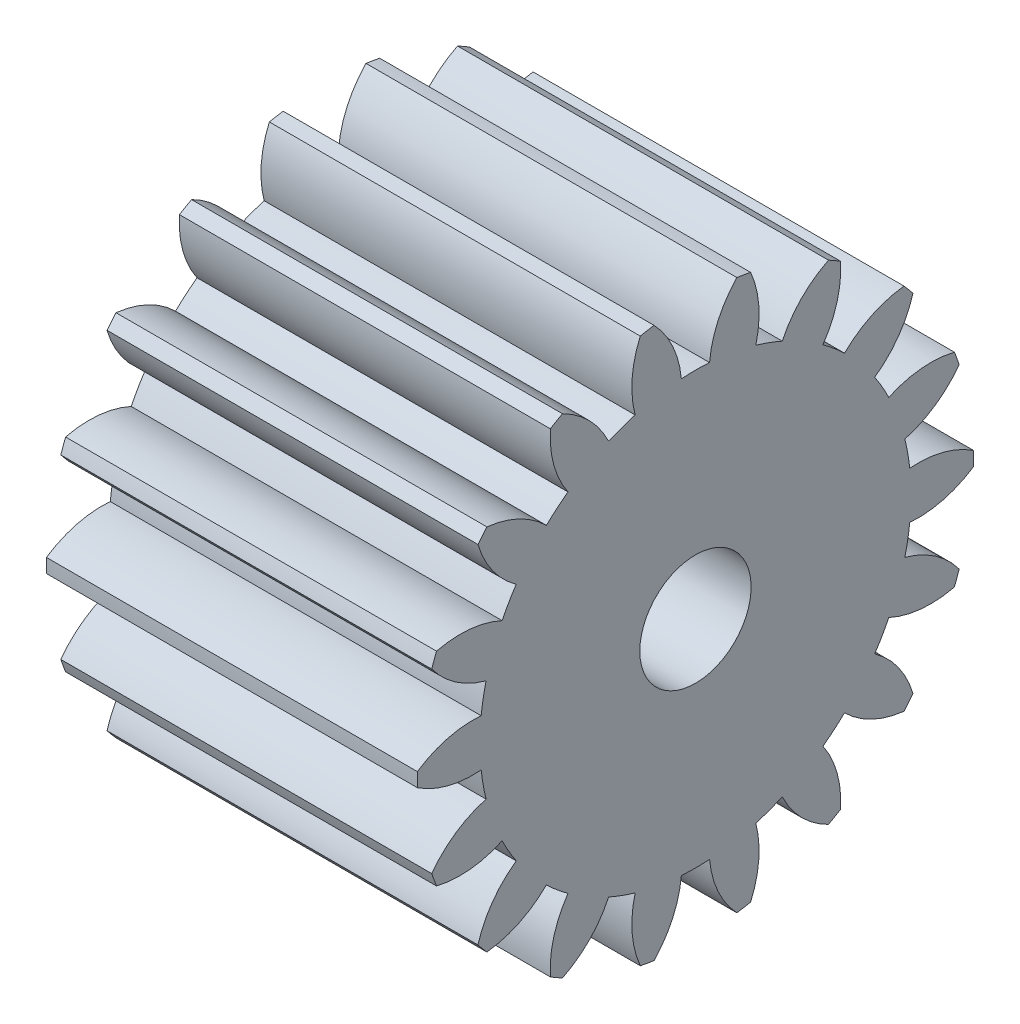
SolidWorks part; units mm, degrees
ref_plane "Plane1" through (0, 0, 0) normal (0, 0, 1) x (1, 0, 0)
ref_plane "Plane2" through (0, 0, 0) normal (0, 1, 0) x (1, 0, 0)
ref_plane "Plane3" through (0, 0, 0) normal (1, 0, 0) x (0, 0, -1)
other "Configuration Table"
sketch "HoldingSke" plane through (0, 0, 0) normal (0, 1, 0) x (1, 0, 0)
  line L0 (0, 0) -> (0.634, -0.206)
  line L1 (-15, 0) -> (100, 0) construction
  line L2 (0, 0) -> (-2.1039, 2.3779)
  line L3 (0, 0) -> (-11.863, 4.5341)
  line L4 (0, 0) -> (8.2133, 2.6687)
  line L5 (0, 0) -> (-46.8476, -17.4728)
  line L6 (0, 0) -> (-16.5793, -11.1861)
  line L7 (-2.1039, 2.3779) -> (8.6586, 51.2059)
  line L8 (-76.2, 54.61) -> (-75.2, 54.61)
  line L9 (-71.009, 38.7566) -> (-53.1078, 45.2721)
  line L10 (-76.2, 71.12) -> (104.1128, 71.12)
  line L11 (0, 0) -> (-20, 0)
  line L12 (-76.2, 101.6) -> (-76.147, 101.6)
  line L13 (24.9733, 27.94) -> (52.9518, 28.4284)
  line L14 (24.9733, 27.94) -> (24.9743, 27.94)
  line L15 (24.9733, 27.94) -> (100.4006, 29.5858)
  line L16 (-63.627, -1.5) -> (-12.827, -1.5)
  circle A0 centre (0, 0) radius 3
  circle A1 centre (0, 0) radius 11.624
  circle A2 centre (0, 0) radius 37.5
  circle A3 centre (0, 0) radius 3
  dimension "MHD" = 23.248
  dimension "Hub_dia" = 75
  dimension "Bore" = 6
  dimension "MBD" = 6
  dimension "Num_teeth" = 18
  dimension "Pitch" = 0.6667
  dimension "Overall_len" = 50
  dimension "Show_teeth" = 18
  dimension "Thickness" = 20
  dimension "OAL" = 50.0001
  dimension "T_dim" = 1
  dimension "Ap" = 20
  dimension "H" = 19.05
  dimension "Pitch_radius" = 180.3128
  dimension "Width" = 20
  dimension "Backlash" = 0.053
  dimension "Addendum_fac" = 1
  dimension "Dedendum_fac" = 1.25
  dimension "Clearance_fac" = 0.25
  dimension "Dedendum_add" = 0.001
  dimension "Module" = 1.5
sketch "BasProSke" plane through (0, 0, 0) normal (0, 1, 0) x (1, 0, 0)
  line L0 (-10, 0) -> (60, 0) construction
  line L1 (0, 0) -> (0, 15)
  line L2 (0, 0) -> (20, 0)
  line L3 (20, 0) -> (20, 15)
  line L4 (20, 15) -> (0, 15)
  dimension "Thickness" = 20
  dimension "Diameter" = 30
revolve "Base-Revolve" add sketch "BasProSke" angle 360 about L0
sketch "TooCutSke" plane through (0, 0, 0) normal (1, 0, 0) x (0, 0, -1)
  line L1 (0, 0) -> (0, 107) construction
  line L2 (0, 0) -> (-1.2693, 13.4402) construction
  line L3 (0, 0) -> (-4.6734, 26.504) construction
  line L4 (-1.2693, 13.4402) -> (-2.3367, 13.252) construction
  arc A0 (0.76, 11.5991) -> (-0.76, 11.5991) centre (0, 0) ccw
  arc A1 (2.2542, 14.8553) -> (-2.2542, 14.8553) centre (0, 0) ccw
  circle A2 centre (0, 0) radius 13.5 construction
  circle A3 centre (0, 0) radius 12.6859 construction
  arc A4 (-0.76, 11.5991) -> (-2.2542, 14.8553) centre (-6.1371, 11.1026) ccw
  arc A5 (2.2542, 14.8553) -> (0.76, 11.5991) centre (6.1371, 11.1026) ccw
  dimension "Root_dia" = 23.248
  dimension "Overcut_dia" = 30.0508
  dimension "Pitch_dia" = 27
  dimension "Base_dia" = 25.3717
  dimension "Flank_rad" = 5.4
  dimension "Half_ang" = 10
  dimension "Half_CT" = 1.0839
extrude "ToothCut" cut sketch "TooCutSke" along normal through all
fillet "Breaks" [suppressed] radius 0.03
fillet "RootFillets" [suppressed] radius 0.376
pattern_circular "TeethCuts" count 18 every 20 about axis through (-10, 0, 0) along (1, 0, 0) of "ToothCut", "RootFillets", "Breaks"
sketch "HubNeaOneSke" plane through (0, 0, 0) normal (-1, 0, 0) x (0, 0, 1)
  circle A0 centre (0, 0) radius 11.624
  dimension "Diameter" = 23.248
extrude "HubNearOne" [suppressed] add sketch "HubNeaOneSke" along normal blind 30.0001
sketch "HubNeaBotSke" plane through (0, 0, 0) normal (-1, 0, 0) x (0, 0, 1)
  circle A0 centre (0, 0) radius 11.624
  dimension "Diameter" = 23.248
extrude "HubNearBoth" [suppressed] add sketch "HubNeaBotSke" along normal blind 15
ref_plane "FarPln" through (20, 0, 0) normal (1, 0, 0) x (0, 0, -1)
sketch "HubFarSke" plane through (20, 0, 0) normal (1, 0, 0) x (0, 0, -1)
  circle A0 centre (0, 0) radius 11.624
  dimension "Diameter" = 23.248
extrude "HubFar" [suppressed] add sketch "HubFarSke" along normal blind 15
sketch "BorSke" plane through (0, 0, 0) normal (1, 0, 0) x (0, 0, -1)
  circle A0 centre (0, 0) radius 3
  dimension "Diameter" = 6
extrude "Bore" cut sketch "BorSke" along normal mid plane 100.0001
sketch "KeySke" plane through (0, 0, 0) normal (1, 0, 0) x (0, 0, -1)
  line L0 (-1, 0) -> (-1, 4)
  line L1 (-1, 4) -> (1, 4)
  line L2 (1, 4) -> (1, 0)
  line L3 (0, 0) -> (0, 34) construction
  line L4 (-1, 0) -> (1, 0)
  dimension "Offset" = 4
extrude "Keyway" [suppressed] cut sketch "KeySke" along normal mid plane 100.0001
pattern_circular "Keyway2" [suppressed] count 2 every 90 about axis through (-10, 0, 0) along (1, 0, 0)
equation "' \"Module@HoldingSke\" = 6.35"
equation "' \"Num_teeth@HoldingSke\" = 12"
equation "' \"Ap@HoldingSke\" =  20"
equation "' \"Ap@HoldingSke\" = 20"
equation "' \"Width@HoldingSke\" = 0.5 * 25.4"
equation "' \"Hub_dia@HoldingSke\"= 1 * 25.4"
equation "' \"Hub_dia@HoldingSke\" = 1 * 25.4"
equation "' \"Overall_len@HoldingSke\" = 1.0 * 25.4"
equation "' \"Bore@HoldingSke\" = 0.75 * 25.4"
equation "' \"T_dim@HoldingSke\" = 0.1 * 25.4"
equation "' \"Width@KeySke\" = 0.25 * 25.4"
equation "' \"Show_teeth@HoldingSke\" = 13"
equation "' \"Backlash@HoldingSke\" = 0.009 * 25.4"
equation "' \"Addendum_fac@HoldingSke\" = 1.0"
equation "' \"Dedendum_fac@HoldingSke\" = 1.25"
equation "' \"Dedendum_add@HoldingSke\" = 0.00005 * 25.4"
equation "' \"Clearance_fac@HoldingSke\" = 0.25"
equation "\"Pitch@HoldingSke\" = 1 / \"Module@HoldingSke\""
equation "\"Overcut_dia@TooCutSke\" = (\"Num_teeth@HoldingSke\" + 2 * \"Addendum_fac@HoldingSke\") / \"Pitch@HoldingSke\" + 0.002 * 25.4"
equation "\"Pitch_dia@TooCutSke\" = \"Num_teeth@HoldingSke\" / \"Pitch@HoldingSke\""
equation "\"Base_dia@TooCutSke\" = \"Num_teeth@HoldingSke\" / \"Pitch@HoldingSke\" * cos((\"Ap@HoldingSke\"  * 3.14159265 / 180))"
equation "\"Root_dia@TooCutSke\" = (\"Num_teeth@HoldingSke\" + 2) / \"Pitch@HoldingSke\" - 2 * (\"Addendum_fac@HoldingSke\" + \"Dedendum_fac@HoldingSke\") / \"Pitch@HoldingSke\" - \"Dedendum_add@HoldingSke\" * 2"
equation "\"Half_ang@TooCutSke\" = 180 / \"Num_teeth@HoldingSke\""
equation "\"Half_CT@TooCutSke\" = \"Num_teeth@HoldingSke\" / \"Pitch@HoldingSke\" * sin((3.14159265 / 2 / \"Num_teeth@HoldingSke\")) / 2 - 7 * \"Backlash@HoldingSke\" / 4"
equation "\"Flank_rad@TooCutSke\" = \"Num_teeth@HoldingSke\" / \"Pitch@HoldingSke\" / 5"
equation "\"Radius@RootFillets\" = \"Clearance_fac@HoldingSke\" / \"Pitch@HoldingSke\" + \"Dedendum_add@HoldingSke\""
equation "\"Break_rad@Breaks\" = 0.02 / \"Pitch@HoldingSke\""
equation "\"Thickness@HoldingSke\" = \"Width@HoldingSke\""
equation "\"OAL@HoldingSke\" = \"Thickness@HoldingSke\""
equation "\"MHD@HoldingSke\" = (\"Num_teeth@HoldingSke\" + 2) / \"Pitch@HoldingSke\" - 2 * (\"Addendum_fac@HoldingSke\" + \"Dedendum_fac@HoldingSke\")  / \"Pitch@HoldingSke\" - \"Dedendum_add@HoldingSke\" * 2"
equation "\"MBD@HoldingSke\" = (\"Num_teeth@HoldingSke\" + 2) / \"Pitch@HoldingSke\" - 2 * (\"Addendum_fac@HoldingSke\" + \"Dedendum_fac@HoldingSke\")  / \"Pitch@HoldingSke\" - \"Dedendum_add@HoldingSke\" * 2 - 0.002 * 25.4"
equation "\"MHD@HoldingSke\" = ((sgn( \"MHD@HoldingSke\" - \"Hub_dia@HoldingSke\" )-1)*( \"MHD@HoldingSke\" - \"Hub_dia@HoldingSke\" ))/-2+ \"Hub_dia@HoldingSke\""
equation "\"MBD@HoldingSke\" = ((sgn( \"MBD@HoldingSke\" - \"Bore@HoldingSke\" )-1)*( \"MBD@HoldingSke\" - \"Bore@HoldingSke\" ))/-2+ \"Bore@HoldingSke\""
equation "\"OAL@HoldingSke\" = ((sgn( \"OAL@HoldingSke\" - \"Overall_len@HoldingSke\" )+1)*( \"OAL@HoldingSke\" - \"Overall_len@HoldingSke\" ))/2 + \"Overall_len@HoldingSke\" + 0.000002 * 25.4"
equation "\"Num_teeth@TeethCuts\" = int( \"Show_teeth@HoldingSke\" ) + 1"
equation "\"Num_teeth@TeethCuts\" = ((sgn( \"Num_teeth@TeethCuts\" - \"Num_teeth@HoldingSke\" )-1)*( \"Num_teeth@TeethCuts\" - \"Num_teeth@HoldingSke\" ))/-2+ \"Num_teeth@HoldingSke\""
equation "\"Num_teeth@TeethCuts\" = ((sgn( \"Num_teeth@TeethCuts\" - 2.0)+1)*( \"Num_teeth@TeethCuts\" - 2.0))/2 +2.0"
equation "\"Angle@TeethCuts\" = 360.0 / \"Num_teeth@HoldingSke\""
equation "\"Diameter@BasProSke\" = (\"Num_teeth@HoldingSke\" + 2 * \"Addendum_fac@HoldingSke\") / \"Pitch@HoldingSke\""
equation "\"Thickness@BasProSke\"  = \"Thickness@HoldingSke\""
equation "' \"Fillet_rad@BasProSke\" =  \"Thickness@HoldingSke\" * 0.05"
equation "' \"Fillet_rad@BasProSke\" = \"Thickness@HoldingSke\" * 0.05"
equation "\"MHD@HoldingSke\" = ((sgn( \"MHD@HoldingSke\" - \"Root_dia@TooCutSke\" )-1)*( \"MHD@HoldingSke\" - \"Root_dia@TooCutSke\" ))/-2+ \"Root_dia@TooCutSke\""
equation "\"Diameter@HubNeaOneSke\" = \"MHD@HoldingSke\""
equation "\"Length@HubNearOne\" = \"OAL@HoldingSke\" - \"Thickness@BasProSke\""
equation "\"Diameter@HubNeaBotSke\" = \"MHD@HoldingSke\""
equation "\"Length@HubNearBoth\" = ( \"OAL@HoldingSke\" - \"Thickness@BasProSke\" ) / 2.0"
equation "\"Thickness@FarPln\" = \"Thickness@BasProSke\""
equation "\"Diameter@HubFarSke\" = \"MHD@HoldingSke\""
equation "\"Length@HubFar\" = ( \"OAL@HoldingSke\" - \"Thickness@BasProSke\" ) / 2.0"
equation "\"Diameter@BorSke\" = \"MBD@HoldingSke\""
equation "\"D1@Bore\" = \"OAL@HoldingSke\" * 2.0"
equation "\"D1@Keyway\" = \"OAL@HoldingSke\" * 2.0"
equation "\"Offset@KeySke\" = \"T_dim@HoldingSke\" + \"MBD@HoldingSke\" / 2.0"
